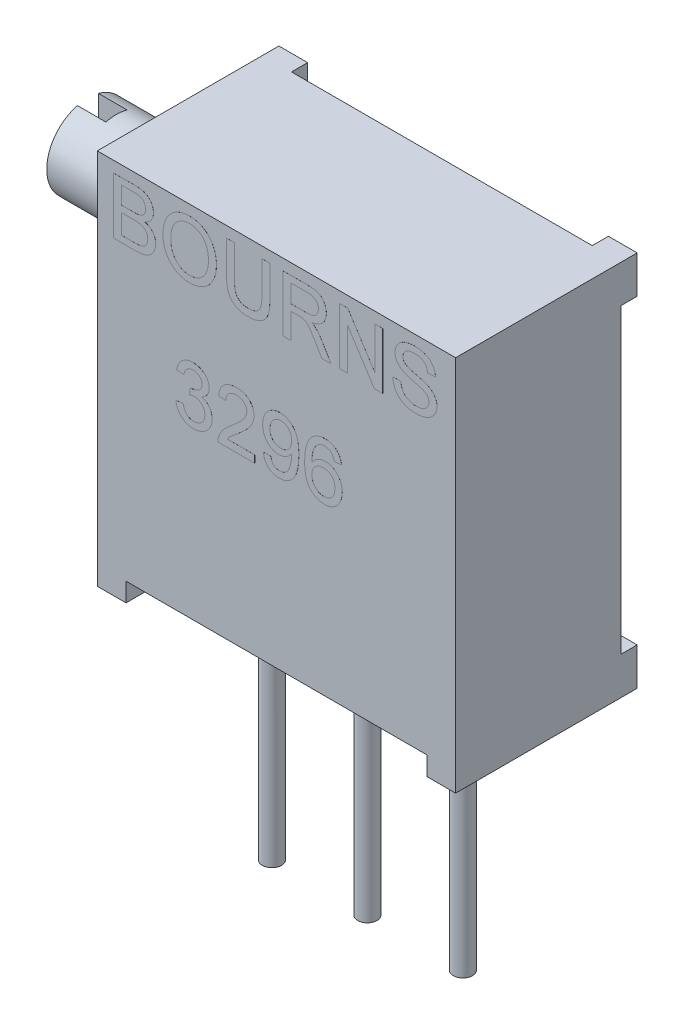
SolidWorks part; units mm, degrees
ref_plane "Plane1" through (0, 0, 0) normal (0, 0, 1) x (1, 0, 0)
ref_plane "Plane2" through (0, 0, 0) normal (0, 1, 0) x (1, 0, 0)
ref_plane "Plane3" through (0, 0, 0) normal (1, 0, 0) x (0, 0, -1)
sketch "Sketch1" plane through (0, 0, 0) normal (0, 0, 1) x (1, 0, 0)
  line L1 (-4.765, 0) -> (4.765, 0)
  line L2 (-4.765, 0) -> (-4.765, 10.03)
  line L3 (-4.765, 10.03) -> (4.765, 10.03)
  line L4 (4.765, 0) -> (4.765, 10.03)
  dimension "D1" = 9.53
  dimension "D2" = 10.03
extrude "Extrude1" add sketch "Sketch1" along normal blind 4.4
sketch "Sketch2" plane through (0, 0, 4.4) normal (0, 0, 1) x (1, 0, 0)
  line L0 (-4.765, 0) -> (4.765, 0) construction
  line L1 (-4, 0) -> (4, 0)
  line L2 (-4, 0) -> (-4, 0.5)
  line L3 (-4, 0.5) -> (4, 0.5)
  line L4 (4, 0) -> (4, 0.5)
  dimension "D1" = 8
  dimension "D2" = 0.5
extrude "Cut-Extrude1" cut sketch "Sketch2" against normal through all
sketch "Sketch3" plane through (0, 0, 0) normal (0, 0, -1) x (-1, 0, 0)
  line L1 (-4.765, 0) -> (-4, 0)
  line L2 (-4.765, 0) -> (-4.765, 1)
  line L3 (-4.765, 1) -> (-4, 1)
  line L4 (-4, 0) -> (-4, 1)
  line L5 (4.765, 0) -> (4, 0)
  line L6 (4.765, 0) -> (4.765, 1)
  line L7 (4.765, 1) -> (4, 1)
  line L8 (4, 0) -> (4, 1)
  line L9 (4.765, 10.03) -> (4, 10.03)
  line L10 (4.765, 10.03) -> (4.765, 9.03)
  line L11 (4.765, 9.03) -> (4, 9.03)
  line L12 (4, 10.03) -> (4, 9.03)
  line L13 (-4.765, 10.03) -> (-4, 10.03)
  line L14 (-4.765, 10.03) -> (-4.765, 9.03)
  line L15 (-4.765, 9.03) -> (-4, 9.03)
  line L16 (-4, 10.03) -> (-4, 9.03)
  dimension "D1" = 1
  dimension "D2" = 1
extrude "Extrude2" add sketch "Sketch3" along normal blind 0.43
sketch "Sketch4" plane through (0, 0.5, 0) normal (0, -1, 0) x (1, 0, 0)
  line L0 (0, 0) -> (0, 1.98) construction
  line L1 (-2.54, 1.98) -> (2.54, 1.98) construction
  line L2 (4.765, -0.43) -> (4, -0.43) construction
  circle A0 centre (2.54, 1.98) radius 0.255
  circle A1 centre (0, 1.98) radius 0.255
  circle A2 centre (-2.54, 1.98) radius 0.255
  dimension "D4" = 0.51
  dimension "D1" = 2.41
  dimension "D2" = 2.54
  dimension "D3" = 2.54
extrude "Extrude3" add sketch "Sketch4" along normal blind 6.9
sketch "Sketch5" plane through (0, 10.03, 0) normal (0, 1, 0) x (-1, 0, 0)
  line L0 (-4.765, 4.4) -> (4.765, 4.4) construction
  line L1 (-4.765, 4.4) -> (-4.765, -0.43) construction
  circle A0 centre (-3.495, 3.13) radius 1.095
  dimension "D3" = 2.19
  dimension "D1" = 1.27
  dimension "D2" = 1.27
sketch "Sketch7" plane through (0, 0, 4.4) normal (0, 0, 1) x (1, 0, 0)
  text T0 "BOURNS\r\n   3296" font "Arial" height 1.5
extrude "Extrude5" add sketch "Sketch7" along normal blind 0.001
sketch "Sketch9" plane through (0, 0.5, 0) normal (0, -1, 0) x (1, 0, 0)
  line L0 (-2.54, 0.71) -> (2.54, 0.71) construction
  line L1 (0, 0) -> (0, 3.25) construction
  line L2 (-4, -0.43) -> (-4.765, -0.43) construction
  circle A0 centre (-2.54, 0.71) radius 0.255
  circle A1 centre (0, 3.25) radius 0.255
  circle A2 centre (2.54, 0.71) radius 0.255
  dimension "D5" = 0.51
  dimension "D1" = 1.14
  dimension "D2" = 2.54
  dimension "D3" = 2.54
  dimension "D4" = 2.54
sketch "1" plane through (-4.765, 5.115, 6.5543) normal (-1, 0, 0) x (0, 0, 1)
  line L2 (-2.1543, 4.915) -> (-6.9843, 4.915) construction
  line L3 (-2.1543, 4.915) -> (-2.1543, -5.115) construction
  circle A0 centre (-3.4243, 3.645) radius 1.095
  dimension "D3" = 2.19
  dimension "D1" = 1.27
  dimension "D2" = 1.27
extrude "Extrude8" add sketch "1" along normal blind 1.52
sketch "2" plane through (-6.285, 5.115, 6.5543) normal (-1, 0, 0) x (0, 0, 1)
  line L0 (-3.4243, 3.645) -> (-3.4243, 1.593) construction
  line L1 (-3.1443, 1.593) -> (-3.7043, 1.593)
  line L2 (-3.1443, 1.593) -> (-3.1443, 5.9157)
  line L3 (-3.1443, 5.9157) -> (-3.7043, 5.9157)
  line L4 (-3.7043, 1.593) -> (-3.7043, 5.9157)
  dimension "D1" = 0.56
extrude "Cut-Extrude3" cut sketch "2" against normal blind 0.76
